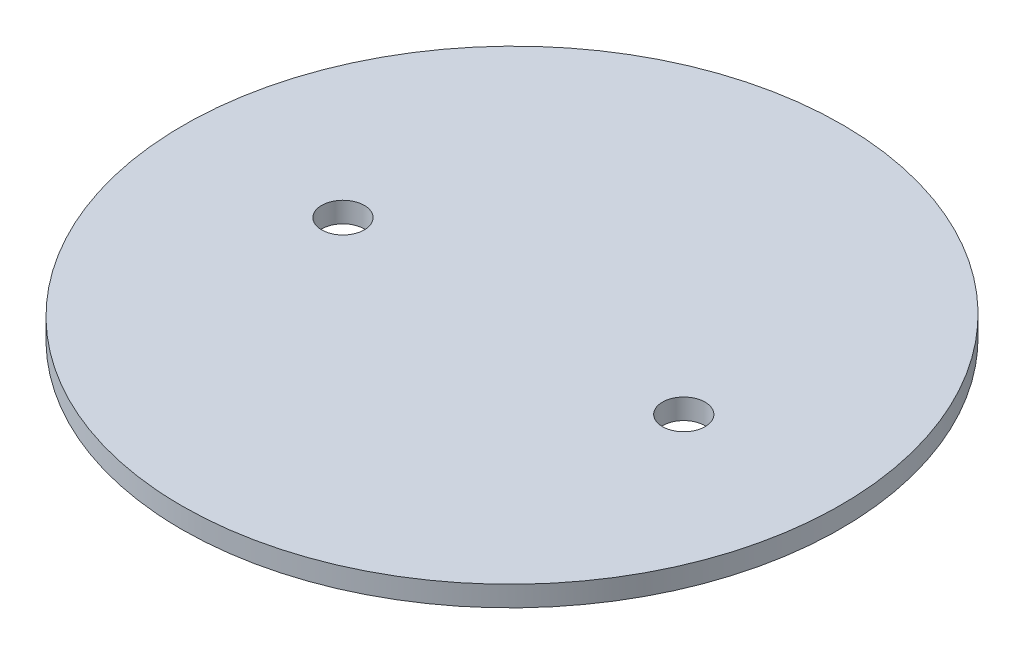
SolidWorks part; units mm, degrees
material "AISI 316 Annealed Stainless Steel Bar (SS)"
ref_plane "Front Plane" through (0, 0, 0) normal (0, 0, 1) x (1, 0, 0)
ref_plane "Top Plane" through (0, 0, 0) normal (0, 1, 0) x (1, 0, 0)
ref_plane "Right Plane" through (0, 0, 0) normal (1, 0, 0) x (0, 0, -1)
sketch "Sketch1" plane through (0, 0, 0) normal (0, 1, 0) x (1, 0, 0)
  line L0 (-140.0993, 0) -> (140.0993, 0) construction
  line L1 (0, 162.2757) -> (0, -162.2757) construction
  circle A0 centre (-49.6, 0) radius 6.25
  circle A1 centre (50.4, 0) radius 6.25
  ellipse E0 centre (0, 0) end of major axis (0, -96.9) minor radius 96.5
  point P4 (0, 0)
  point P8 (0, 0)
  dimension "D3" = 12.5
  dimension "D4" = 12.5
  dimension "D1" = 193.8
  dimension "D2" = 193
  dimension "D5" = 100
  dimension "D6" = 46.9
extrude "Boss-Extrude1" add sketch "Sketch1" along normal mid plane 6
